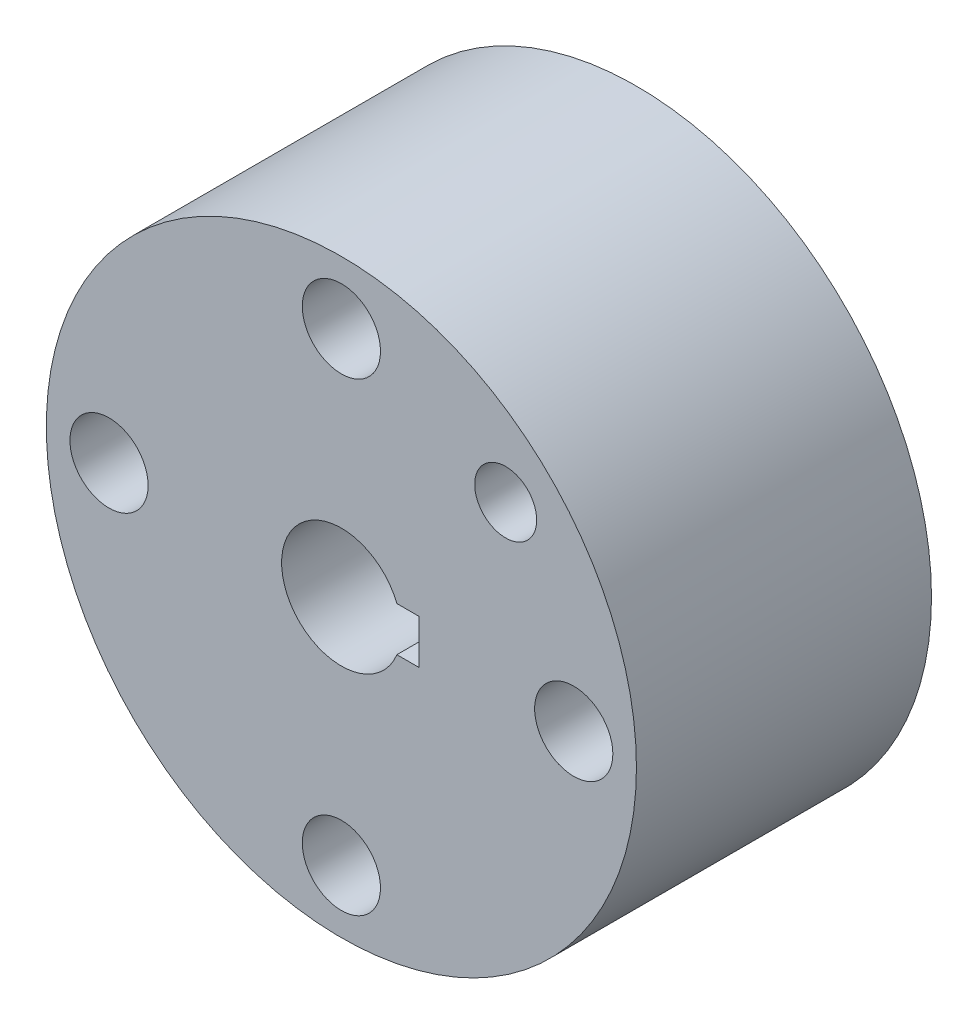
SolidWorks part; units mm, degrees
ref_plane "Front Plane" through (0, 0, 0) normal (0, 0, 1) x (1, 0, 0)
ref_plane "Top Plane" through (0, 0, 0) normal (0, 1, 0) x (1, 0, 0)
ref_plane "Right Plane" through (0, 0, 0) normal (1, 0, 0) x (0, 0, -1)
sketch "Sketch1" plane through (0, 0, 0) normal (0, 0, 1) x (1, 0, 0)
  line L0 (0, 0) -> (11.1369, 11.1369) construction
  line L1 (-4.05, 0) -> (-4.05, 1.7265) construction
  line L2 (2.85, -1.5) -> (5.25, -1.5)
  line L3 (2.85, -1.5) -> (2.85, 1.5)
  line L4 (2.85, 1.5) -> (5.25, 1.5)
  line L5 (5.25, -1.5) -> (5.25, 1.5)
  line L6 (2.85, -1.5) -> (5.25, 1.5) construction
  line L7 (2.85, 1.5) -> (5.25, -1.5) construction
  circle A0 centre (0, 0) radius 20
  circle A1 centre (0, 0) radius 10
  circle A2 centre (0, 0) radius 15.75 construction
  circle A3 centre (0, 15.75) radius 2.65
  circle A4 centre (15.75, 0) radius 2.65
  circle A5 centre (0, -15.75) radius 2.65
  circle A6 centre (-15.75, 0) radius 2.65
  circle A7 centre (11.1369, 11.1369) radius 2.1
  circle A8 centre (0, 0) radius 4.05
  point P16 (0, 0)
  point P17 (4.05, 0)
  dimension "D1" = 40
  dimension "D2" = 20
  dimension "D3" = 31.5
  dimension "D4" = 5.3
  dimension "D6" = 4.2
  dimension "D7" = 8.1
  dimension "D8" = 9.3
  dimension "D9" = 3
  dimension "D5" = 4
extrude "Boss-Extrude1" add sketch "Sketch1" along normal blind 20 contours A0 A7 A6 A5 A4 A3 A1 | A1 A8 L4 L5 L2
sketch "Skizze1" plane through (0, 0, 0) normal (0, 0, -1) x (-1, 0, 0)
  circle A0 centre (0, 0) radius 10
  dimension "D1" = 20
extrude "Schnitt-Linear austragen1" cut sketch "Skizze1" against normal offset from surface (8 mm away) 12 up to face at (13.2369, 11.1369, 20)
